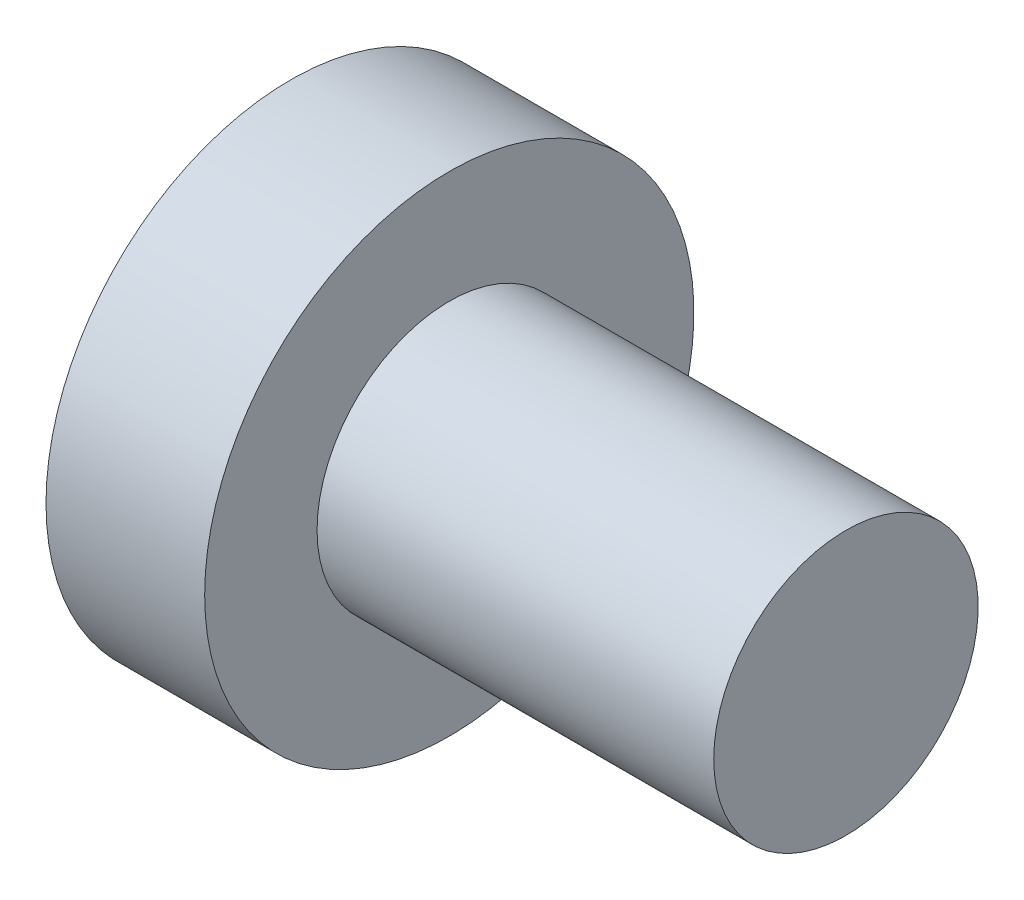
SolidWorks part; units mm, degrees
material "5052-H32"
ref_plane "正面" through (0, 0, 0) normal (0, 0, 1) x (1, 0, 0)
ref_plane "平面" through (0, 0, 0) normal (0, 1, 0) x (1, 0, 0)
ref_plane "右側面" through (0, 0, 0) normal (1, 0, 0) x (0, 0, -1)
sketch "ｽｹｯﾁ1" plane through (0, 0, 0) normal (0, 0, 1) x (1, 0, 0)
  line L0 (0, 0) -> (20, 0) construction
  line L1 (-6, 0) -> (-6, 9.25)
  line L2 (-6, 9.25) -> (0, 9.25)
  line L3 (0, 9.25) -> (0, 5)
  line L4 (0, 5) -> (15, 5)
  line L5 (15, 5) -> (15, 0)
  line L6 (15, 0) -> (-6, 0)
  dimension "D1" = 6
  dimension "D2" = 15
  dimension "D3" = 9.25
  dimension "D4" = 5
revolve "ペネトレータ" add sketch "ｽｹｯﾁ1" angle 360 about L0
equation "\"PEN_FLANGE_T\" = 6"
equation "\"D1@ｽｹｯﾁ1\" = \"PEN_FLANGE_T\""
equation "\"CAP_PLATE_T\" = 12"
equation "\"PEN_TAIL\" = 3"
equation "\"D2@ｽｹｯﾁ1\" = \"CAP_PLATE_T\" + \"PEN_TAIL\""
equation "\"PEN_FLANGE_OD\" = 18.5"
equation "\"D3@ｽｹｯﾁ1\" = \"PEN_FLANGE_OD\" / 2"
equation "\"PEN_SHANK_D\" = 10"
equation "\"D4@ｽｹｯﾁ1\" = \"PEN_SHANK_D\" / 2"
